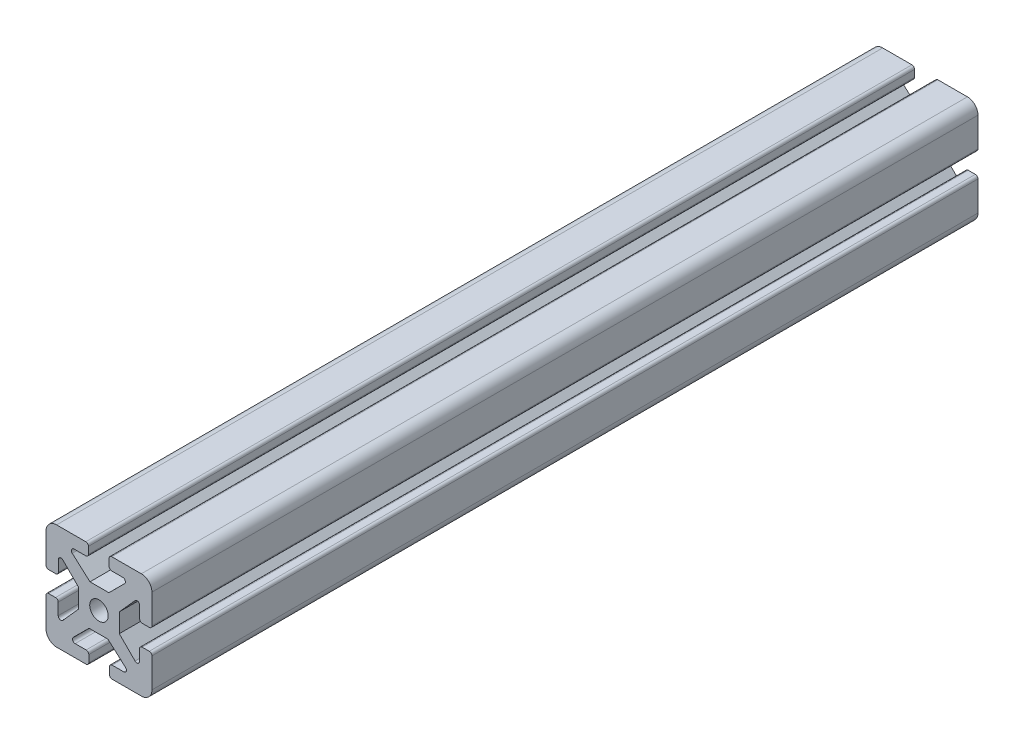
SolidWorks part; units mm, degrees
ref_plane "Front Plane" through (0, 0, 0) normal (0, 0, 1) x (1, 0, 0)
ref_plane "Top Plane" through (0, 0, 0) normal (0, 1, 0) x (1, 0, 0)
ref_plane "Right Plane" through (0, 0, 0) normal (1, 0, 0) x (0, 0, -1)
sketch "Sketch2" plane through (0, 0, 0) normal (0, 0, 1) x (1, 0, 0)
  line L0 (46.607, 139.3199) -> (233.0351, 139.3199) construction
  line L1 (0, 40) -> (40, 0) construction
  line L2 (0, 0) -> (40, 0) construction
  line L3 (0, 0) -> (0, 40) construction
  line L4 (0, 40) -> (40, 40) construction
  line L5 (40, 0) -> (40, 40) construction
  line L6 (0, 0) -> (40, 40) construction
  line L7 (19.4883, 27.6847) -> (23.7499, 27.6847)
  line L8 (23.7499, 27.6847) -> (29.6997, 33.625)
  line L9 (28.9931, 35.3327) -> (24.8456, 35.3327)
  line L10 (23.8456, 36.3327) -> (23.8456, 39)
  line L11 (24.8456, 40) -> (36, 40)
  line L12 (40, 36) -> (40, 24.9611)
  line L13 (39, 23.9611) -> (36.3883, 23.9611)
  line L14 (35.3883, 24.9611) -> (35.3883, 29.4086)
  line L15 (33.6417, 30.0739) -> (27.6847, 23.3888)
  line L16 (27.6847, 23.3888) -> (27.6847, 20.5117)
  line L17 (27.6847, 16.2501) -> (33.625, 10.3003)
  line L18 (30.0739, 6.3583) -> (23.3888, 12.3153)
  line L19 (27.6847, 20.5117) -> (27.6847, 16.2501)
  line L20 (35.3327, 11.0069) -> (35.3327, 15.1544)
  line L21 (36.3327, 16.1544) -> (39, 16.1544)
  line L22 (40, 15.1544) -> (40, 4)
  line L23 (36, 0) -> (24.9611, 0)
  line L24 (23.9611, 1) -> (23.9611, 3.6117)
  line L25 (24.9611, 4.6117) -> (29.4086, 4.6117)
  line L26 (23.3888, 12.3153) -> (20.5117, 12.3153)
  line L27 (16.2501, 12.3153) -> (10.3003, 6.375)
  line L28 (6.3583, 9.9261) -> (12.3153, 16.6112)
  line L29 (20.5117, 12.3153) -> (16.2501, 12.3153)
  line L30 (11.0069, 4.6673) -> (15.1544, 4.6673)
  line L31 (16.1544, 3.6673) -> (16.1544, 1)
  line L32 (15.1544, 0) -> (4, 0)
  line L33 (0, 4) -> (0, 15.0389)
  line L34 (1, 16.0389) -> (3.6117, 16.0389)
  line L35 (4.6117, 15.0389) -> (4.6117, 10.5914)
  line L36 (12.3153, 16.6112) -> (12.3153, 19.4883)
  line L37 (12.3153, 23.7499) -> (6.375, 29.6997)
  line L38 (9.9261, 33.6417) -> (16.6112, 27.6847)
  line L39 (12.3153, 19.4883) -> (12.3153, 23.7499)
  line L40 (4.6673, 28.9931) -> (4.6673, 24.8456)
  line L41 (3.6673, 23.8456) -> (1, 23.8456)
  line L42 (0, 24.8456) -> (0, 36)
  line L43 (4, 40) -> (15.0389, 40)
  line L44 (16.0389, 39) -> (16.0389, 36.3883)
  line L45 (15.0389, 35.3883) -> (10.5914, 35.3883)
  line L46 (16.6112, 27.6847) -> (19.4883, 27.6847)
  circle A1 centre (20, 20) radius 3.4925
  arc A2 (40, 24.9611) -> (39, 23.9611) centre (39, 24.9611) cw
  arc A3 (36.3883, 23.9611) -> (35.3883, 24.9611) centre (36.3883, 24.9611) cw
  arc A4 (24.8456, 35.3327) -> (23.8456, 36.3327) centre (24.8456, 36.3327) cw
  arc A5 (23.8456, 39) -> (24.8456, 40) centre (24.8456, 39) cw
  arc A6 (29.6997, 33.625) -> (28.9931, 35.3327) centre (28.9931, 34.3327) ccw
  arc A7 (35.3883, 29.4086) -> (33.6417, 30.0739) centre (34.3883, 29.4086) ccw
  arc A8 (40, 36) -> (36, 40) centre (36, 36) ccw
  arc A9 (35.3327, 15.1544) -> (36.3327, 16.1544) centre (36.3327, 15.1544) cw
  arc A10 (39, 16.1544) -> (40, 15.1544) centre (39, 15.1544) cw
  arc A11 (36, 0) -> (40, 4) centre (36, 4) ccw
  arc A12 (24.9611, 0) -> (23.9611, 1) centre (24.9611, 1) cw
  arc A13 (23.9611, 3.6117) -> (24.9611, 4.6117) centre (24.9611, 3.6117) cw
  arc A14 (29.4086, 4.6117) -> (30.0739, 6.3583) centre (29.4086, 5.6117) ccw
  arc A15 (33.625, 10.3003) -> (35.3327, 11.0069) centre (34.3327, 11.0069) ccw
  arc A16 (15.1544, 4.6673) -> (16.1544, 3.6673) centre (15.1544, 3.6673) cw
  arc A17 (16.1544, 1) -> (15.1544, 0) centre (15.1544, 1) cw
  arc A18 (0, 4) -> (4, 0) centre (4, 4) ccw
  arc A19 (0, 15.0389) -> (1, 16.0389) centre (1, 15.0389) cw
  arc A20 (3.6117, 16.0389) -> (4.6117, 15.0389) centre (3.6117, 15.0389) cw
  arc A21 (4.6117, 10.5914) -> (6.3583, 9.9261) centre (5.6117, 10.5914) ccw
  arc A22 (10.3003, 6.375) -> (11.0069, 4.6673) centre (11.0069, 5.6673) ccw
  arc A23 (4.6673, 24.8456) -> (3.6673, 23.8456) centre (3.6673, 24.8456) cw
  arc A24 (1, 23.8456) -> (0, 24.8456) centre (1, 24.8456) cw
  arc A25 (4, 40) -> (0, 36) centre (4, 36) ccw
  arc A26 (15.0389, 40) -> (16.0389, 39) centre (15.0389, 39) cw
  arc A27 (16.0389, 36.3883) -> (15.0389, 35.3883) centre (15.0389, 36.3883) cw
  arc A28 (10.5914, 35.3883) -> (9.9261, 33.6417) centre (10.5914, 34.3883) ccw
  arc A29 (6.375, 29.6997) -> (4.6673, 28.9931) centre (5.6673, 28.9931) ccw
  point P24 (40, 23.9611)
  point P31 (23.8456, 40)
  dimension "D1" = 40
  dimension "D3" = 1
  dimension "D4" = 4
  dimension "D2" = 40
  dimension "D5" = 4
extrude "Boss-Extrude1" add sketch "Sketch2" along normal blind 312
